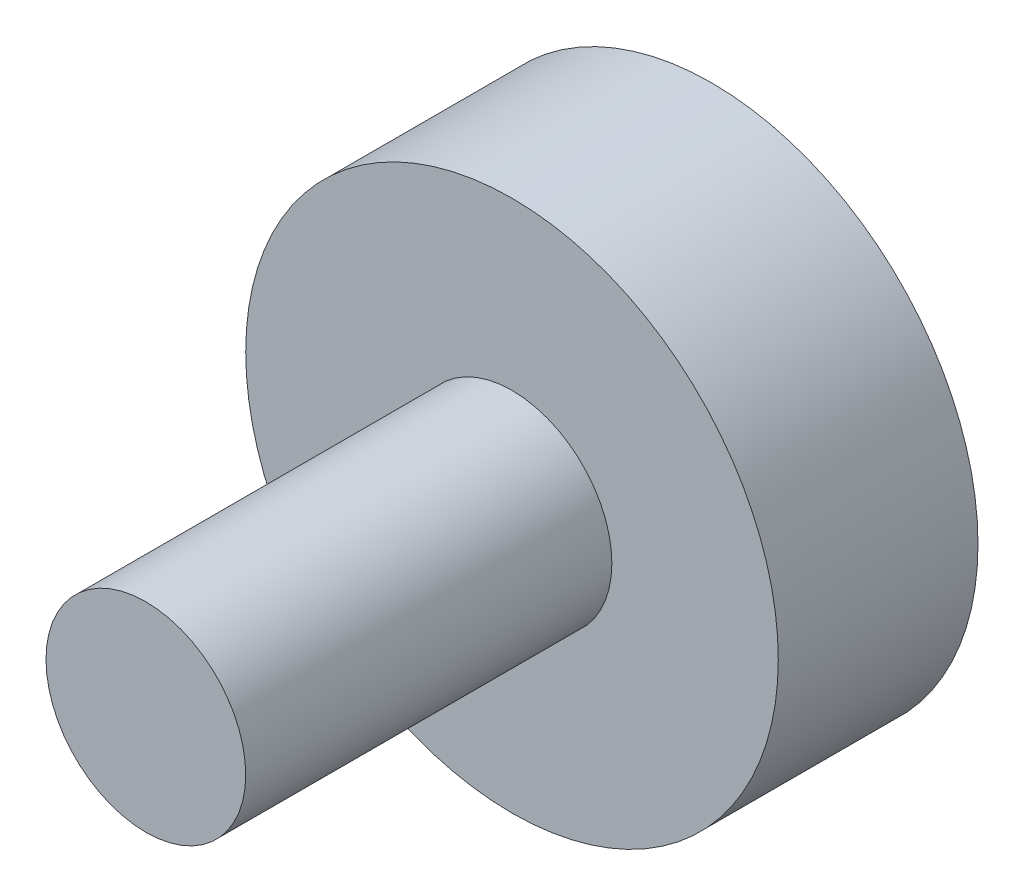
SolidWorks part; units mm, degrees
ref_plane "Front Plane" through (0, 0, 0) normal (0, 0, 1) x (1, 0, 0)
ref_plane "Top Plane" through (0, 0, 0) normal (0, 1, 0) x (1, 0, 0)
ref_plane "Right Plane" through (0, 0, 0) normal (1, 0, 0) x (0, 0, -1)
sketch "Sketch1" plane through (0, 0, 0) normal (0, 0, 1) x (1, 0, 0)
  circle A0 centre (0, 0) radius 101.6
  point P2 (0, 0)
  dimension "D1" = 203.2
extrude "Boss-Extrude1" add sketch "Sketch1" along normal blind 76.2
sketch "Sketch2" plane through (0, 0, 76.2) normal (0, 0, 1) x (1, 0, 0)
  circle A0 centre (0, 0) radius 38.1
  dimension "D1" = 76.2
extrude "Boss-Extrude2" add sketch "Sketch2" along normal blind 139.7
